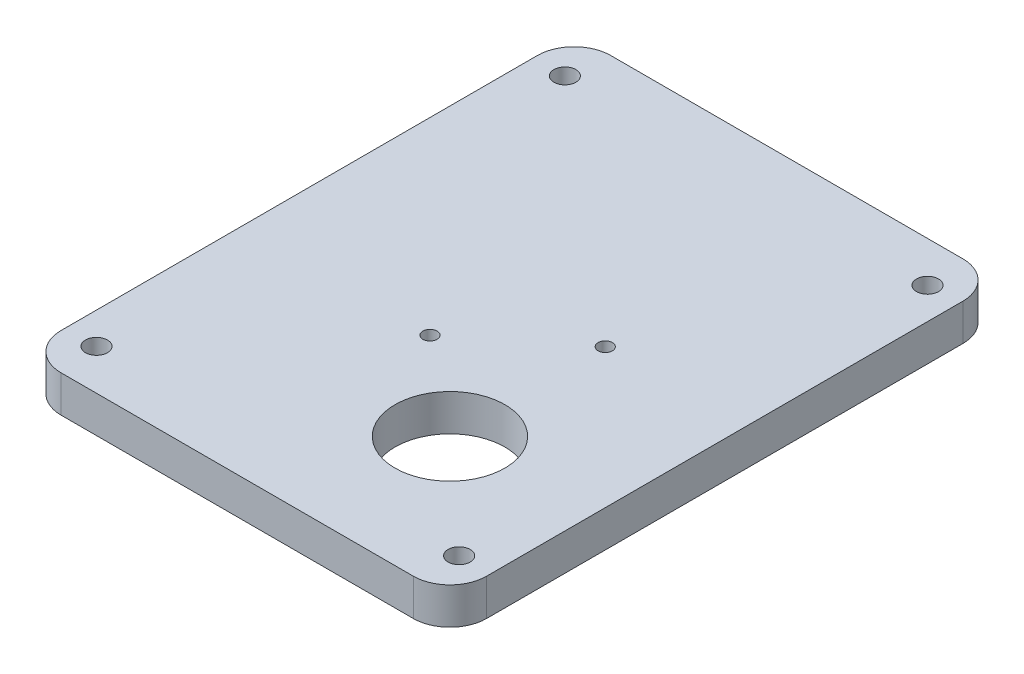
SolidWorks part; units mm, degrees
ref_plane "Front Plane" through (0, 0, 0) normal (0, 0, 1) x (1, 0, 0)
ref_plane "Top Plane" through (0, 0, 0) normal (0, 1, 0) x (1, 0, 0)
ref_plane "Right Plane" through (0, 0, 0) normal (1, 0, 0) x (0, 0, -1)
sketch "Sketch1" plane through (0, 0, 0) normal (0, 1, 0) x (1, 0, 0)
  line L0 (0, 0) -> (10, -13.7477) construction
  line L1 (10, -13.7477) -> (-3.3043, -24.3305) construction
  line L2 (-3.3043, -24.3305) -> (10, -34.9132) construction
  line L9 (-29, 21) -> (-29, -53.9132)
  line L10 (-29, -53.9132) -> (29, -53.9132)
  line L11 (29, -53.9132) -> (29, 21)
  line L12 (29, 21) -> (-29, 21)
  circle A2 centre (0, 0) radius 6.5 construction
  circle A4 centre (-3.3043, -24.3305) radius 12 construction
  circle A5 centre (10, -13.7477) radius 12 construction
  circle A13 centre (0, 0) radius 7
  circle A18 centre (0, 0) radius 18 construction
  circle A29 centre (10, -34.9132) radius 12 construction
  circle A30 centre (10, -13.7477) radius 0.975
  circle A31 centre (-3.3043, -24.3305) radius 0.975
  circle A32 centre (10, -34.9132) radius 3.2
  point P13 (22, -34.9132)
  point P15 (-3.3043, -36.3305)
  point P17 (0, 18)
  point P20 (0, 0)
  point P27 (0, 21)
  point P31 (0, 0)
  point P32 (-1.2518, 24.0011)
  point P48 (10, -46.9132)
  dimension "D2" = 6.4
  dimension "D3" = 13
  dimension "D4" = 17
  dimension "D5" = 14
  dimension "D6" = 24
  dimension "D9" = 58
  dimension "D10" = 3
  dimension "D11" = 36
  dimension "D12" = 7
  dimension "D7" = 19
  dimension "D1" = 1.95
  dimension "D8" = 77
extrude "Boss-Extrude1" add sketch "Sketch1" along normal blind 5
sketch "Sketch6" plane through (0, 0, 0) normal (0, 1, 0) x (1, 0, 0)
  line L0 (-29, 21) -> (29, -53.9132) construction
  line L1 (-29, -53.9132) -> (29, 21) construction
  line L2 (29, -53.9132) -> (29, 21) construction
  line L3 (-19.2407, -48.9132) -> (19.2407, -48.9132)
  line L4 (-24, -42.9249) -> (-24, 10.0117)
  line L5 (-19.2407, 16) -> (19.2407, 16)
  line L6 (24, -42.9249) -> (24, 10.0117)
  line L7 (-17.4628, -39.0117) -> (24.7147, 15.465) construction
  line L8 (-15.7648, 14.3966) -> (15.4234, -46.6416) construction
  line L9 (0, -16.4566) -> (55.9921, -16.4566) construction
  line L10 (-29, -53.9132) -> (29, -53.9132)
  line L11 (-29, -53.9132) -> (-29, 21)
  line L12 (-29, 21) -> (29, 21)
  line L13 (29, -53.9132) -> (29, 21)
  line L14 (-29, -53.9132) -> (29, 21) construction
  line L15 (-29, 21) -> (29, -53.9132) construction
  line L16 (0, -16.4566) -> (0, 26.1978) construction
  circle A0 centre (24.7147, 15.465) radius 1.5
  arc A1 (19.2407, 16) -> (24, 10.0117) centre (24.7147, 15.465) ccw
  circle A2 centre (24.7147, -48.3783) radius 1.5
  arc A3 (19.2407, -48.9132) -> (24, -42.9249) centre (24.7147, -48.3783) cw
  arc A4 (-19.2407, 16) -> (-24, 10.0117) centre (-24.7147, 15.465) cw
  circle A5 centre (-24.7147, 15.465) radius 1.5
  circle A6 centre (-24.7147, -48.3783) radius 1.5
  arc A7 (-19.2407, -48.9132) -> (-24, -42.9249) centre (-24.7147, -48.3783) ccw
  point P8 (0, -16.4566)
  point P15 (0, -16.4566)
  dimension "D2" = 3
  dimension "D3" = 4
  dimension "D1" = 5
  dimension "D4" = 7
  dimension "5" = 5
fillet "Fillet1" radius 5 4 edges at (29, 2.5, -21) (29, 2.5, 53.9132) (-29, 2.5, 53.9132) (-29, 2.5, -21)
extrude "Cut-Extrude9" cut sketch "Sketch6" along normal blind 14 contours A0 | A5 | A2 | A6
sketch "Sketch7" plane through (0, 0, 0) normal (0, 1, 0) x (1, 0, 0)
  circle A0 centre (10, -34.9132) radius 7.49
  dimension "D1" = 14.98
extrude "Cut-Extrude10" cut sketch "Sketch7" along normal up to surface (5 mm away) up to face at (-24.7147, 5, 49.8783)
